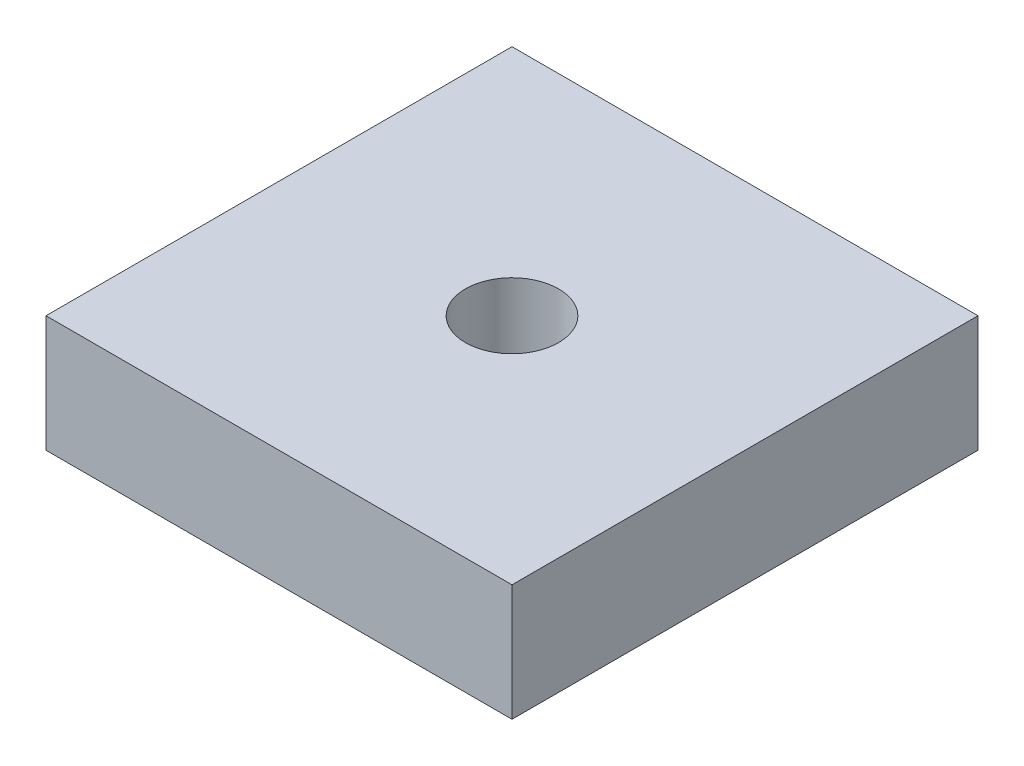
SolidWorks part; units mm, degrees
ref_plane "Front Plane" through (0, 0, 0) normal (0, 0, 1) x (1, 0, 0)
ref_plane "Top Plane" through (0, 0, 0) normal (0, 1, 0) x (1, 0, 0)
ref_plane "Right Plane" through (0, 0, 0) normal (1, 0, 0) x (0, 0, -1)
sketch "Sketch1" plane through (0, 0, 0) normal (0, 1, 0) x (1, 0, 0)
  line L1 (-5, 5) -> (5, 5)
  line L2 (-5, 5) -> (-5, -5)
  line L3 (-5, -5) -> (5, -5)
  line L4 (5, 5) -> (5, -5)
  circle A0 centre (0, 0) radius 1
  dimension "D3" = 2
  dimension "D1" = 10
  dimension "D2" = 10
  dimension "D4" = 5
  dimension "D5" = 5
extrude "Boss-Extrude1" add sketch "Sketch1" along normal blind 2.5
